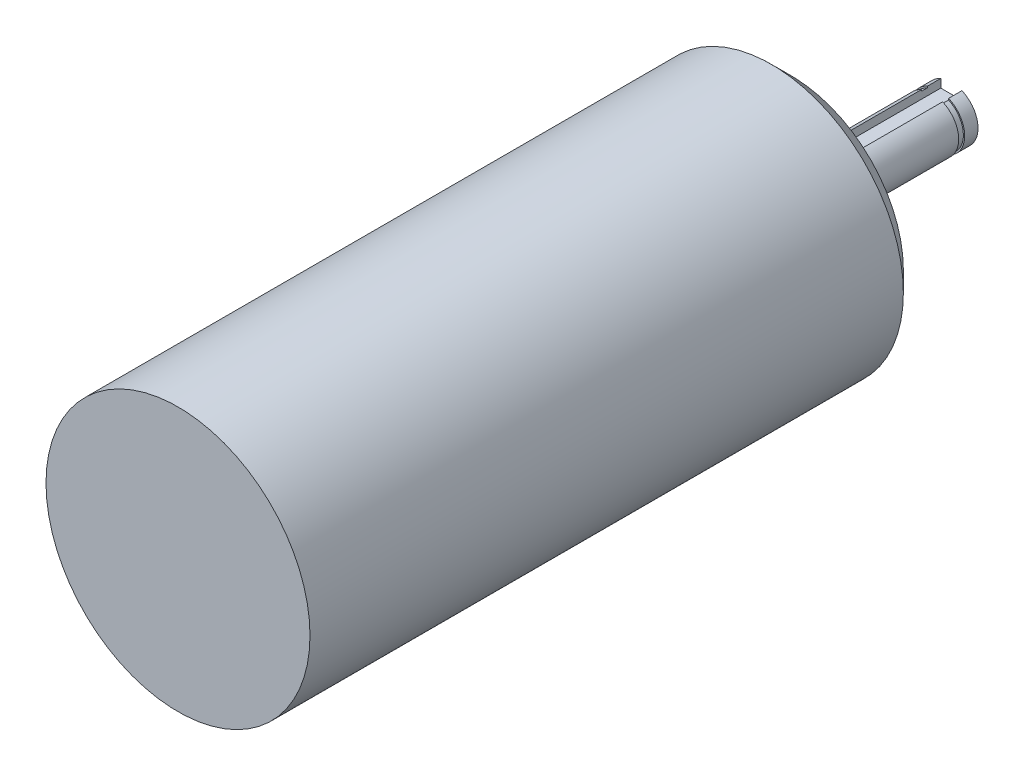
SolidWorks part; units mm, degrees
ref_plane "Front Plane" through (0, 0, 0) normal (0, 0, 1) x (1, 0, 0)
ref_plane "Top Plane" through (0, 0, 0) normal (0, 1, 0) x (1, 0, 0)
ref_plane "Right Plane" through (0, 0, 0) normal (1, 0, 0) x (0, 0, -1)
sketch "Sketch1" plane through (0, 0, 0) normal (0, 0, 1) x (1, 0, 0)
  circle A0 centre (0, 0) radius 19.8
  dimension "D1" = 39.6
extrude "Boss-Extrude1" add sketch "Sketch1" along normal blind 92
sketch "face mounting holes" plane through (0, 0, 0) normal (0, 0, -1) x (-1, 0, 0)
  point P0 (0, 12.5)
  point P4 (12.5, 0)
  point P5 (0, -12.5)
  point P6 (-12.5, 0)
  point P7 (0, 0)
  dimension "D2" = 25
  dimension "D1" = 4
hole_wizard "M4x0.7 Tapped Hole1" positions "Sketch3" profile "Sketch5" tap size "M4x0.7" standard "ANSI Metric"
sketch "Sketch3" plane through (0, 0, 0) normal (0, 0, -1) x (-1, 0, 0)
  point P0 (0, 12.5)
  point P3 (-12.5, 0)
  point P6 (0, -12.5)
  point P9 (12.5, 0)
sketch "Sketch5" plane through (0, 12.5, 0) normal (1, 0, 0) x (0, 1, 0)
  line L0 (0, 0) -> (0, 4.9914)
  line L1 (0, 4.9914) -> (1.65, 4)
  line L2 (1.65, 4) -> (1.65, 0.375)
  line L3 (1.65, 0.375) -> (2.025, 0)
  line L5 (2.025, 0) -> (0, 0)
  line L6 (-1.65, 0.375) -> (-2.025, 0) construction
  line L10 (0, 4.9914) -> (-1.65, 4) construction
  line L11 (0, -6.35) -> (0, 107.95) construction
  dimension "Tap Drill Dia." = 3.3
  dimension "Tap Drill Depth" = 4
  dimension "Near C'Sink Dia." = 4.05
  dimension "Near C'Sink Angle" = 90
  dimension "Drill Angle" = 118
cosmetic thread "Hole Thread1" parameters "D1"=4, "D2"=4
cosmetic thread "Hole Thread2" parameters "D1"=4, "D2"=4
cosmetic thread "Hole Thread3" parameters "D1"=4, "D2"=4
cosmetic thread "Hole Thread4" parameters "D1"=4, "D2"=4
sketch "Sketch6" plane through (0, 0, 0) normal (0, 0, -1) x (-1, 0, 0)
  circle A0 centre (0, 0) radius 4
  dimension "D1" = 8
extrude "Boss-Extrude2" add sketch "Sketch6" along normal blind 24
chamfer "Chamfer1" distance 3 angle 45 1 edges at (19.8, 0, 0)
sketch "Sketch7" plane through (0, 0, -24) normal (0, 0, -1) x (-1, 0, 0)
  line L1 (-1.5875, 2.4125) -> (1.5875, 2.4125)
  line L2 (-1.5875, 2.4125) -> (-1.5875, 5.5875)
  line L3 (-1.5875, 5.5875) -> (1.5875, 5.5875)
  line L4 (1.5875, 2.4125) -> (1.5875, 5.5875)
  line L5 (-1.5875, 2.4125) -> (1.5875, 5.5875) construction
  line L6 (-1.5875, 5.5875) -> (1.5875, 2.4125) construction
  circle A0 centre (0, 0) radius 4 construction
  point P0 (0, 4)
  dimension "D1" = 3.175
  dimension "D2" = 3.175
extrude "Cut-Extrude1" cut sketch "Sketch7" against normal blind 19
ref_plane "Plane1" through (0, 0, -22) normal (0, 0, -1) x (-1, 0, 0)
sketch "Sketch8" plane through (0, 0, -22) normal (0, 0, -1) x (-1, 0, 0)
  circle A0 centre (0, 0) radius 3.8
  circle A1 centre (0, 0) radius 4
  arc A2 (-1.5875, 3.6715) -> (1.5875, 3.6715) centre (0, 0) ccw construction
  dimension "D1" = 7.6
extrude "Cut-Extrude2" cut sketch "Sketch8" against normal blind 0.9
equation "\"D1@Sketch7\"=0.125in"
equation "\"D2@Sketch7\"=0.125in"
